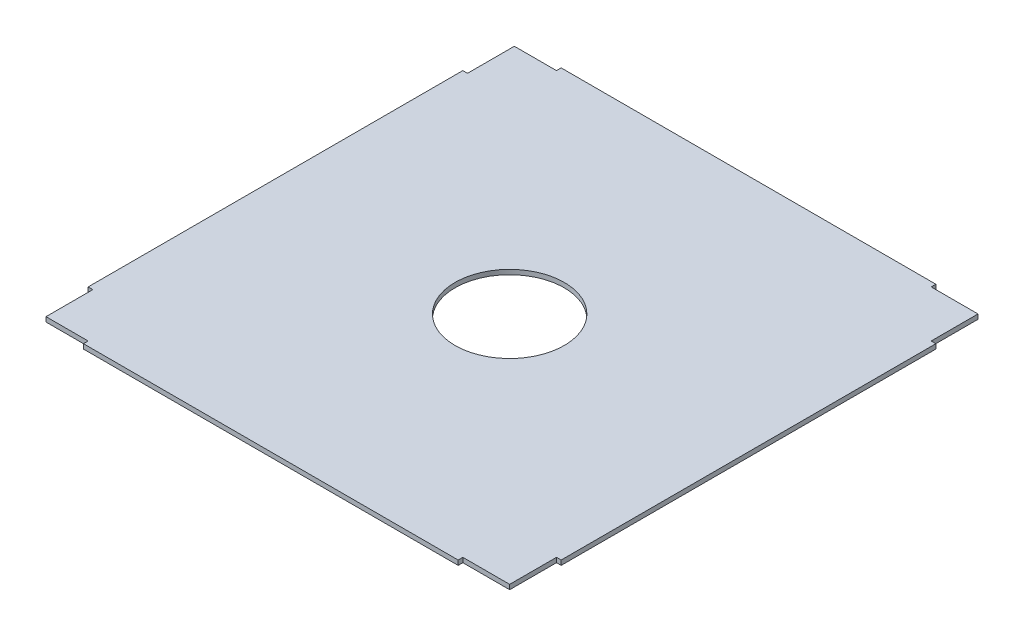
SolidWorks part; units mm, degrees
ref_plane "Front Plane" through (0, 0, 0) normal (0, 0, 1) x (1, 0, 0)
ref_plane "Top Plane" through (0, 0, 0) normal (0, 1, 0) x (1, 0, 0)
ref_plane "Right Plane" through (0, 0, 0) normal (1, 0, 0) x (0, 0, -1)
sketch "Sketch1" plane through (0, 0, 0) normal (0, 1, 0) x (1, 0, 0)
  line L0 (-267, 136.5677) -> (-240, 136.5677)
  line L1 (-240, 136.5677) -> (-240, 139.5677)
  line L2 (-240, 139.5677) -> (0, 139.5677)
  line L3 (0, 139.5677) -> (0, 136.5677)
  line L4 (0, 136.5677) -> (30, 136.5677)
  line L5 (30, 136.5677) -> (30, 106.5677)
  line L6 (30, -163.4323) -> (0, -163.4323)
  line L7 (0, -163.4323) -> (0, -166.4323)
  line L8 (0, -166.4323) -> (-240, -166.4323)
  line L9 (-240, -166.4323) -> (-240, -163.4323)
  line L10 (-240, -163.4323) -> (-267, -163.4323)
  line L11 (-267, -163.4323) -> (-267, -133.4323)
  line L12 (-267, -133.4323) -> (-270, -133.4323)
  line L13 (-267, 106.5677) -> (-267, 136.5677)
  line L14 (30, -133.4323) -> (30, -163.4323)
  line L15 (-270, -133.4323) -> (-270, 106.5677)
  line L16 (-270, 106.5677) -> (-267, 106.5677)
  line L17 (30, -133.4323) -> (33, -133.4323)
  line L18 (33, -133.4323) -> (33, 106.5677)
  line L19 (33, 106.5677) -> (30, 106.5677)
  dimension "D1" = 300
  dimension "D2" = 300
  dimension "D3" = 3
  dimension "D4" = 3
  dimension "D5" = 3
  dimension "D6" = 30
  dimension "D7" = 30
  dimension "D8" = 27
  dimension "D9" = 27
  dimension "D10" = 240
  dimension "D11" = 240
  dimension "D12" = 30
  dimension "D13" = 30
  dimension "D14" = 240
  dimension "D15" = 30
  dimension "D16" = 30
  dimension "D17" = 3
  dimension "D18" = 3
  dimension "D19" = 3
  dimension "D20" = 3
extrude "Boss-Extrude1" add sketch "Sketch1" along normal blind 3
sketch "Sketch2" plane through (0, 3, 0) normal (0, 1, 0) x (1, 0, 0)
  line L0 (0, 139.5677) -> (-240, 139.5677) construction
  line L2 (33, -133.4323) -> (33, 106.5677) construction
  circle A0 centre (-120, -13.4323) radius 35
  dimension "D1" = 70
  dimension "D2" = 153
  dimension "D3" = 153
extrude "Cut-Extrude1" cut sketch "Sketch2" against normal blind 3
